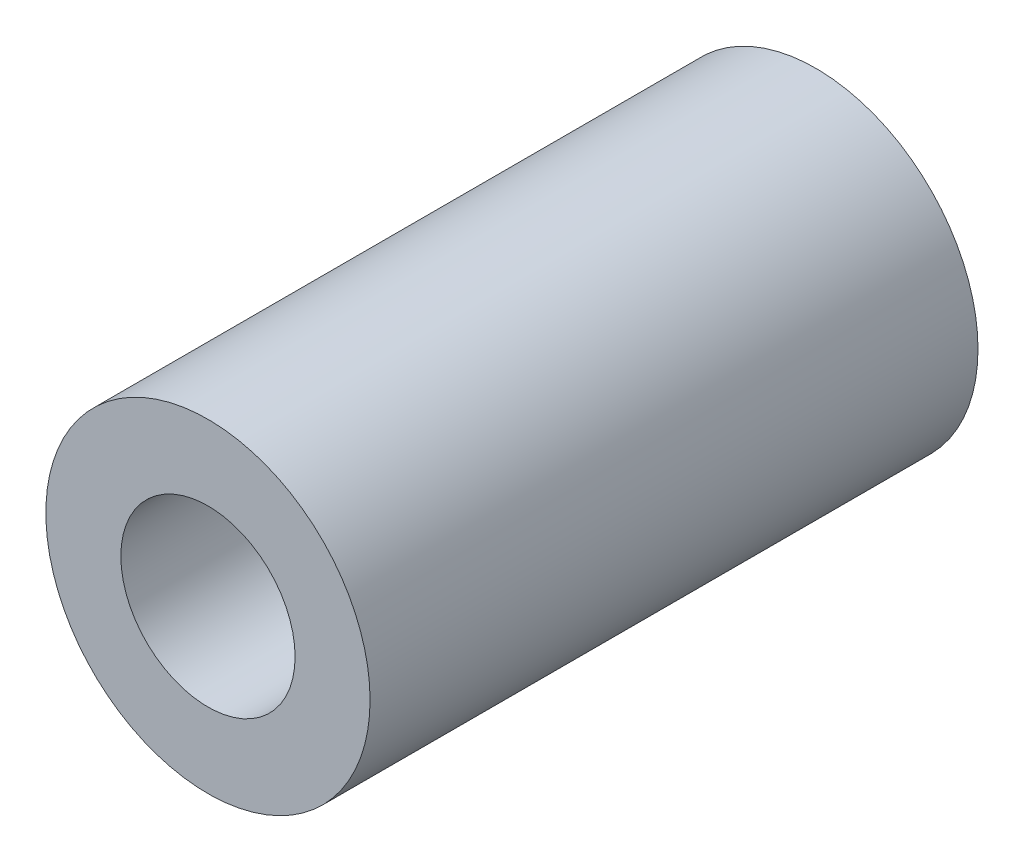
SolidWorks part; units mm, degrees
ref_plane "Спереди" through (0, 0, 0) normal (0, 0, 1) x (1, 0, 0)
ref_plane "Сверху" through (0, 0, 0) normal (0, 1, 0) x (1, 0, 0)
ref_plane "Справа" through (0, 0, 0) normal (1, 0, 0) x (0, 0, -1)
sketch "Эскиз1" plane through (0, 0, 0) normal (0, 0, 1) x (1, 0, 0)
  circle A0 centre (0, 0) radius 4
  circle A1 centre (0, 0) radius 2.15
  dimension "D1" = 8
  dimension "D2" = 4.3
extrude "Бобышка-Вытянуть1" add sketch "Эскиз1" along normal mid plane 15
